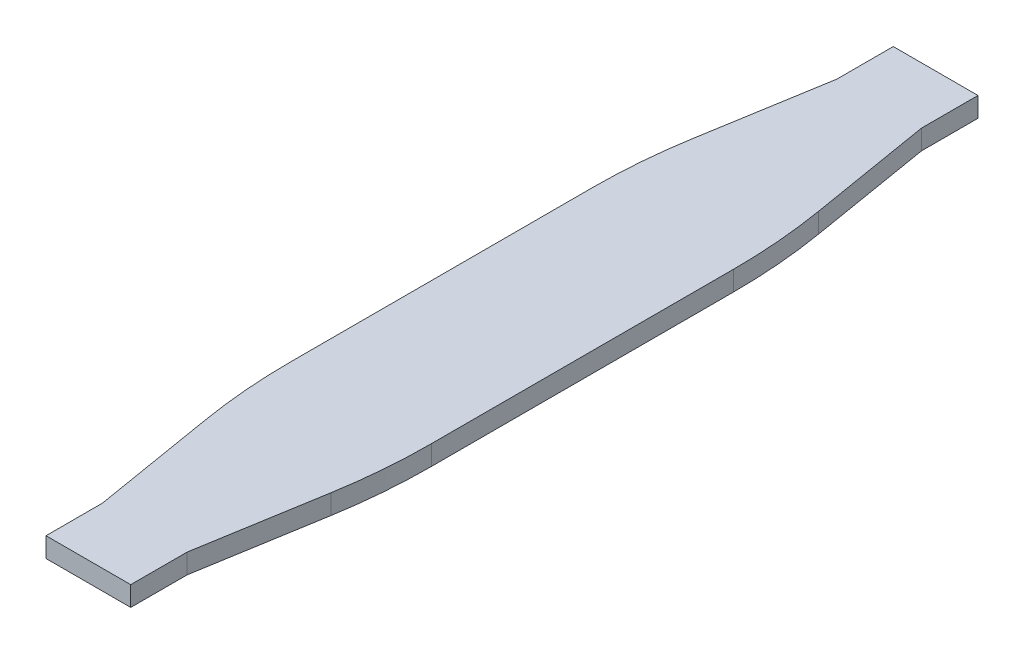
SolidWorks part; units mm, degrees
material "Actuator"
ref_plane "Front Plane" through (0, 0, 0) normal (0, 0, 1) x (1, 0, 0)
ref_plane "Top Plane" through (0, 0, 0) normal (0, 1, 0) x (1, 0, 0)
ref_plane "Right Plane" through (0, 0, 0) normal (1, 0, 0) x (0, 0, -1)
sketch "Sketch1" plane through (0, 0, 0.0021) normal (0, 1, 0) x (1, 0, 0)
  line L0 (65.9572, 129.4957) -> (66.4572, 132.4957)
  line L1 (63.9572, 132.4957) -> (64.4572, 129.4957)
  line L2 (63.9572, 132.4957) -> (66.4572, 132.4957) construction
  line L3 (63.9572, 132.4957) -> (63.9572, 139.4957)
  line L4 (63.9572, 139.4957) -> (64.4572, 142.4957)
  line L5 (64.4572, 142.4957) -> (64.4572, 143.4957)
  line L6 (64.4572, 143.4957) -> (65.9572, 143.4957)
  line L7 (65.9572, 143.4957) -> (65.9572, 142.4957)
  line L8 (65.9572, 142.4957) -> (66.4572, 139.4957)
  line L9 (66.4572, 139.4957) -> (66.4572, 132.4957)
  line L15 (64.4572, 129.4957) -> (64.4572, 128.4957)
  line L16 (64.4572, 128.4957) -> (65.2072, 128.4957)
  line L20 (65.2072, 128.4957) -> (65.9572, 128.4957)
  line L21 (65.9572, 128.4957) -> (65.9572, 129.4957)
  point P0 (65.2072, 132.4957)
  point P12 (65.2072, 143.4957)
  dimension "D1" = 2.5
  dimension "D2" = 3
  dimension "D3" = 1
  dimension "D4" = 1.5
  dimension "D5" = 3
  dimension "D6" = 7
  dimension "D7" = 1
  dimension "D8" = 1.5
extrude "Boss-Extrude1" add sketch "Sketch1" along normal blind 0.35
fillet "Fillet1" radius 10 4 edges at (66.4572, 0.175, -139.4936) (66.4572, 0.175, -132.4936) (63.9572, 0.175, -132.4936) (63.9572, 0.175, -139.4936)
